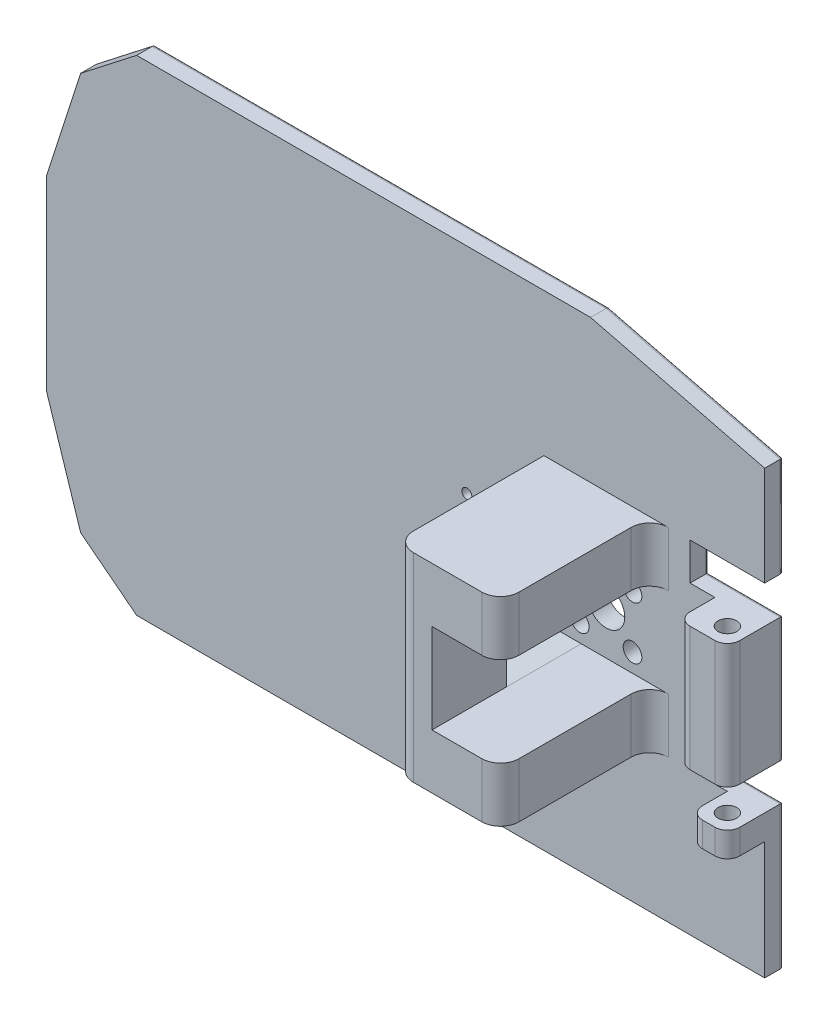
SolidWorks part; units mm, degrees
ref_plane "Front Plane" through (0, 0, 0) normal (0, 0, 1) x (1, 0, 0)
ref_plane "Top Plane" through (0, 0, 0) normal (0, 1, 0) x (1, 0, 0)
ref_plane "Right Plane" through (0, 0, 0) normal (1, 0, 0) x (0, 0, -1)
sketch "Sketch1" plane through (0, 0, 0) normal (0, 0, 1) x (1, 0, 0)
  line L3 (-18.8619, -42.0998) -> (82.1381, -42.0998)
  line L4 (82.1381, 28.9002) -> (82.1381, 12.9002)
  line L8 (-18.8619, 35.9002) -> (-27.8619, 28.9002)
  line L9 (-27.8619, 28.9002) -> (-33.3619, 11.9002)
  line L10 (-18.8619, 35.9002) -> (54.1381, 35.9002)
  line L11 (-33.3619, 11.9002) -> (-33.3619, -18.0998)
  line L13 (-18.8619, -42.0998) -> (-27.8619, -35.0998)
  line L14 (-27.8619, -35.0998) -> (-33.3619, -18.0998)
  line L16 (54.1381, 35.9002) -> (82.1381, 28.9002)
  line L17 (82.1381, -13.0998) -> (70.1381, -13.0998)
  line L18 (70.1381, -13.0998) -> (70.1381, -19.0998)
  line L19 (70.1381, -19.0998) -> (82.1381, -19.0998)
  line L20 (82.1381, 12.9002) -> (70.1381, 12.9002)
  line L21 (70.1381, 12.9002) -> (70.1381, 6.9002)
  line L22 (70.1381, 6.9002) -> (82.1381, 6.9002)
  line L23 (82.1381, 6.9002) -> (82.1381, -13.0998)
  line L24 (82.1381, -19.0998) -> (82.1381, -42.0998)
  point P2 (82.1381, 12.9002)
  point P3 (82.1381, 6.9002)
  point P11 (82.1381, -13.0998)
  point P12 (82.1381, -19.0998)
  dimension "D1" = 30
  dimension "D2" = 23
  dimension "D3" = 6
  dimension "D4" = 20
  dimension "D5" = 23
  dimension "D6" = 6
  dimension "D7" = 12
extrude "Boss-Extrude1" add sketch "Sketch1" along normal blind 3
fillet "Fillet1" radius 0.5 17 edges at (31.6381, -42.0998, 0) (82.1381, -30.5998, 0) (76.1381, -19.0998, 0) (70.1381, -16.0998, 0) (76.1381, -13.0998, 0) (82.1381, -3.0998, 0) (76.1381, 6.9002, 0) (70.1381, 9.9002, 0) (76.1381, 12.9002, 0) (82.1381, 20.9002, 0) (68.1381, 32.4002, 0) (17.6381, 35.9002, 0) (-23.3619, 32.4002, 0) (-30.6119, 20.4002, 0) (-33.3619, -3.0998, 0) (-30.6119, -26.5998, 0) (-23.3619, -38.5998, 0)
sketch "Sketch2" plane through (0, 0, 3) normal (0, 0, 1) x (1, 0, 0)
  line L3 (63.6381, -19.0998) -> (46.6381, -19.0998)
  line L4 (46.6381, -19.0998) -> (46.6381, 12.9002)
  line L5 (46.6381, 12.9002) -> (63.6381, 12.9002)
  line L6 (63.6381, 12.9002) -> (63.6381, 4.1002)
  line L7 (63.6381, -19.0998) -> (63.6381, -10.2998)
  line L8 (63.6381, 4.1002) -> (52.6381, 4.1002)
  line L9 (52.6381, 4.1002) -> (52.6381, -10.2998)
  line L10 (52.6381, -10.2998) -> (63.6381, -10.2998)
  dimension "D3" = 17
  dimension "D4" = 32
  dimension "D5" = 8.8
  dimension "D6" = 8.8
  dimension "D7" = 11
extrude "Boss-Extrude3" add sketch "Sketch2" along normal blind 24 contours L4 L5 L6 L8 L9 L10 L7 L3
fillet "Fillet4" radius 3 1 edges at (46.6381, -3.0998, 27)
fillet "Fillet5" radius 3 2 edges at (63.6381, -14.6998, 27) (63.6381, 8.5002, 27)
fillet "Fillet6" radius 3 2 edges at (63.6381, 8.5002, 3) (63.6381, -14.6998, 3)
sketch "Sketch4" plane through (0, 0, 3) normal (0, 0, 1) x (1, 0, 0)
  line L0 (82.1381, -19.0998) -> (82.1381, -23.0998)
  line L1 (82.1381, -42.0998) -> (82.1381, -19.0998) construction
  line L2 (82.1381, -23.0998) -> (76.1381, -23.0998)
  line L3 (76.1381, -23.0998) -> (76.1381, -19.0998)
  line L6 (76.1381, -19.0998) -> (82.1381, -19.0998)
  dimension "D1" = 4
  dimension "D2" = 6
extrude "Boss-Extrude4" add sketch "Sketch4" along normal blind 6 contours L2 L3 L6 L0
fillet "Fillet7" radius 2 2 edges at (76.1381, -21.0998, 9) (82.1381, -21.0998, 9)
sketch "Sketch5" plane through (0, -19.0998, 0) normal (0, 1, 0) x (1, 0, 0)
  line L0 (79.1381, 0) -> (79.1381, -6)
  line L1 (54.0766, 0) -> (81.6381, 0) construction
  line L2 (76.1381, -6) -> (79.1381, -6)
  line L3 (76.1381, -7) -> (76.1381, -3) construction
  circle A0 centre (79.1381, -6) radius 1.5
  dimension "D3" = 3
  dimension "D1" = 6
  dimension "D2" = 3
sketch "Sketch7" plane through (0, 0, 3) normal (0, 0, 1) x (1, 0, 0)
  line L0 (82.1381, 6.9002) -> (74.1381, 6.9002)
  line L1 (82.1381, 6.9002) -> (70.1381, 6.9002) construction
  line L2 (74.1381, 6.9002) -> (74.1381, -13.0998)
  line L3 (70.1381, -13.0998) -> (82.1381, -13.0998) construction
  line L4 (74.1381, -13.0998) -> (82.1381, -13.0998)
  line L5 (82.1381, -13.0998) -> (82.1381, 6.9002) construction
  line L6 (82.1381, -13.0998) -> (82.1381, 6.9002)
  dimension "D1" = 8
extrude "Boss-Extrude5" add sketch "Sketch7" along normal blind 6
fillet "Fillet8" radius 2 2 edges at (74.1381, -3.0998, 9) (82.1381, -3.0998, 9)
extrude "Cut-Extrude1" cut sketch "Sketch5" along normal blind 31.1375 and the other way blind 7.874 contours A0
sketch "Sketch8" plane through (0, 0, 3) normal (0, 0, 1) x (1, 0, 0)
  line L0 (82.1381, -3.0998) -> (56.6381, -3.0998)
  line L2 (34.2381, -3.0998) -> (82.1381, -3.0998)
  line L3 (82.1381, 6.9002) -> (82.1381, -13.0998) construction
  circle A0 centre (34.2381, -3.0998) radius 2.5
  circle A1 centre (56.6381, -3.0998) radius 3
  dimension "D3" = 5
  dimension "D4" = 6
  dimension "D1" = 25.5
  dimension "D2" = 47.9
sketch "Sketch11" plane through (52.6381, 0, 0) normal (1, 0, 0) x (0, 0, -1)
  line L0 (-3, 4.1002) -> (-15, 4.1002)
  line L1 (-27, 4.1002) -> (-3, 4.1002) construction
  line L2 (-15, 4.1002) -> (-15, -10.3827)
  line L3 (-15, -10.3827) -> (-3, -10.2998)
  line L4 (-3, -10.2998) -> (-3, 4.1002)
  dimension "D1" = 12
extrude "Cut-Extrude2" cut sketch "Sketch11" against normal blind 31.1375
sketch "Sketch12" plane through (0, 0, 3) normal (0, 0, 1) x (1, 0, 0)
  circle A1 centre (56.6381, -3.0998) radius 3
  circle A2 centre (34.2381, -3.0998) radius 2.5
extrude "Cut-Extrude3" cut sketch "Sketch12" against normal blind 31.1375
sketch "Sketch13" plane through (0, 0, 3) normal (0, 0, 1) x (1, 0, 0)
  circle A0 centre (60.8808, 1.1428) radius 1.5
  dimension "D2" = 3
extrude "Cut-Extrude4" cut sketch "Sketch13" against normal blind 31.1375 contours A0
pattern_circular "CirPattern1" count 4 every 90 about axis through (56.6381, -3.0998, 0) along (0, 0, 1) of "Cut-Extrude4"
sketch "Sketch14" plane through (0, 0, 3) normal (0, 0, 1) x (1, 0, 0)
  circle A0 centre (34.2381, 1.4002) radius 0.8
  circle A1 centre (34.2381, -7.5998) radius 0.8
  dimension "D2" = 1.6
  dimension "D3" = 1.6
extrude "Cut-Extrude5" cut sketch "Sketch14" against normal blind 31.1375
